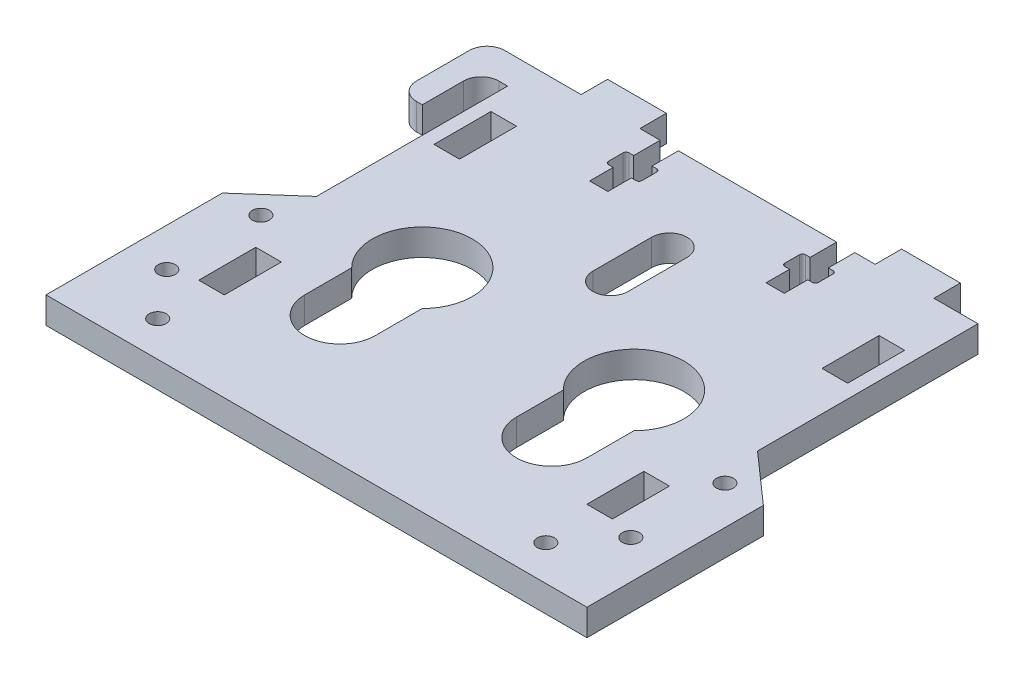
SolidWorks part; units mm, degrees
ref_plane "Front Plane" through (0, 0, 0) normal (0, 0, 1) x (1, 0, 0)
ref_plane "Top Plane" through (0, 0, 0) normal (0, 1, 0) x (1, 0, 0)
ref_plane "Right Plane" through (0, 0, 0) normal (1, 0, 0) x (0, 0, -1)
sketch "Sketch1" plane through (0, 0, 0) normal (0, 1, 0) x (1, 0, 0)
  line L1 (-37.5, 37.5) -> (37.5, 37.5)
  line L2 (-37.5, 37.5) -> (-37.5, -37.5)
  line L3 (-37.5, -37.5) -> (37.5, -37.5)
  line L4 (37.5, 37.5) -> (37.5, -37.5)
  line L5 (-37.5, 37.5) -> (37.5, -37.5) construction
  line L6 (-37.5, -37.5) -> (37.5, 37.5) construction
  point P0 (0, 0)
  dimension "D1" = 75
  dimension "D2" = 75
extrude "MainShape" add sketch "Sketch1" along normal blind 4.5
sketch "Sketch2" plane through (0, 4.5, 0) normal (0, 1, 0) x (1, 0, 0)
  line L0 (0, -37.5) -> (0, 37.5) construction
  line L1 (-37.5, -37.5) -> (37.5, -37.5) construction
  line L2 (37.5, 37.5) -> (-37.5, 37.5) construction
  line L4 (-5, 42) -> (5, 42)
  line L5 (-5, 42) -> (-5, 33)
  line L6 (-5, 33) -> (5, 33)
  line L7 (5, 42) -> (5, 33)
  line L8 (-5, 42) -> (5, 33) construction
  line L9 (-5, 33) -> (5, 42) construction
  dimension "D1" = 10
  dimension "D2" = 4.5
extrude "Tab1" [suppressed] add sketch "Sketch2" against normal through all
sketch "Sketch4" [suppressed] plane through (0, 4.5, 0) normal (0, 1, 0) x (1, 0, 0)
  line L0 (0, 42) -> (0, -37.5) construction
  line L1 (5, 42) -> (-5, 42) construction
  line L2 (-47.5, -37.5) -> (47.5, -37.5) construction
  line L3 (-40, 37.5) -> (-40, 27) construction
  line L4 (-5, 37.5) -> (-47.5, 37.5) construction
  line L5 (-38.25, 27) -> (-41.75, 27) construction
  line L6 (-41.75, 27) -> (-41.75, 37.5) construction
  line L7 (-38.25, 27) -> (-41.75, 27)
  line L8 (-41.75, 27) -> (-41.75, 29.5)
  line L9 (-41.75, 29.5) -> (-42.75, 29.5)
  line L10 (-43, 29.75) -> (-43, 33.45)
  line L11 (-42.75, 33.7) -> (-41.75, 33.7)
  line L12 (-41.75, 33.7) -> (-41.75, 37.5)
  line L13 (-41.75, 37.5) -> (-38.25, 37.5)
  line L14 (-38.25, 27) -> (-38.25, 37.5) construction
  line L15 (-38.25, 33.7) -> (-38.25, 37.5)
  line L16 (-37.25, 33.7) -> (-38.25, 33.7)
  line L17 (-37, 29.75) -> (-37, 33.45)
  line L18 (-38.25, 29.5) -> (-37.25, 29.5)
  line L19 (-38.25, 27) -> (-38.25, 29.5)
  line L20 (38.25, 27) -> (38.25, 37.5) construction
  line L21 (41.75, 27) -> (41.75, 37.5) construction
  line L22 (38.25, 27) -> (41.75, 27) construction
  line L23 (40, 37.5) -> (40, 27) construction
  line L24 (38.25, 27) -> (38.25, 29.5)
  line L25 (38.25, 29.5) -> (37.25, 29.5)
  line L26 (37, 29.75) -> (37, 33.45)
  line L27 (37.25, 33.7) -> (38.25, 33.7)
  line L28 (38.25, 33.7) -> (38.25, 37.5)
  line L29 (41.75, 37.5) -> (38.25, 37.5)
  line L30 (41.75, 33.7) -> (41.75, 37.5)
  line L31 (42.75, 33.7) -> (41.75, 33.7)
  line L32 (43, 29.75) -> (43, 33.45)
  line L33 (41.75, 29.5) -> (42.75, 29.5)
  line L34 (41.75, 27) -> (41.75, 29.5)
  line L35 (38.25, 27) -> (41.75, 27)
  arc A0 (-42.75, 29.5) -> (-43, 29.75) centre (-42.75, 29.75) cw
  arc A1 (-37, 29.75) -> (-37.25, 29.5) centre (-37.25, 29.75) cw
  arc A2 (-37.25, 33.7) -> (-37, 33.45) centre (-37.25, 33.45) cw
  arc A3 (-43, 33.45) -> (-42.75, 33.7) centre (-42.75, 33.45) cw
  arc A4 (43, 33.45) -> (42.75, 33.7) centre (42.75, 33.45) ccw
  arc A5 (37.25, 33.7) -> (37, 33.45) centre (37.25, 33.45) ccw
  arc A6 (37, 29.75) -> (37.25, 29.5) centre (37.25, 29.75) ccw
  arc A7 (42.75, 29.5) -> (43, 29.75) centre (42.75, 29.75) ccw
  point P24 (-43, 29.5)
  point P27 (-37, 29.5)
  point P30 (-37, 33.7)
  point P33 (-43, 33.7)
  point P56 (43, 33.7)
  point P57 (37, 33.7)
  point P58 (37, 29.5)
  point P59 (43, 29.5)
  dimension "D7" = 0.5
  dimension "D1" = 11
  dimension "D2" = 1.55
  dimension "D3" = 3.5
  dimension "D4" = 2.85
  dimension "D5" = 8
  dimension "D6" = 40
extrude "Cut-Extrude2" [suppressed] cut sketch "Sketch4" against normal through all
sketch "Sketch5" plane through (0, 4.5, 0) normal (0, 1, 0) x (1, 0, 0)
  line L0 (0, -37.5) -> (0, 37.5) construction
  line L1 (-37.5, -37.5) -> (37.5, -37.5) construction
  line L3 (33, 37.5) -> (33, -37.5) construction
  line L4 (37.5, 37.5) -> (-37.5, 37.5) construction
  line L5 (-33, 37.5) -> (-33, -37.5) construction
  line L6 (30.825, 27.35) -> (35.175, 27.35)
  line L7 (30.825, 27.35) -> (30.825, 17.65)
  line L8 (30.825, 17.65) -> (35.175, 17.65)
  line L9 (35.175, 27.35) -> (35.175, 17.65)
  line L10 (30.825, 27.35) -> (35.175, 17.65) construction
  line L11 (30.825, 17.65) -> (35.175, 27.35) construction
  line L12 (-30.825, 17.65) -> (-35.175, 27.35) construction
  line L13 (-30.825, 27.35) -> (-35.175, 17.65) construction
  line L14 (-35.175, 27.35) -> (-35.175, 17.65)
  line L15 (-30.825, 17.65) -> (-35.175, 17.65)
  line L16 (-30.825, 27.35) -> (-30.825, 17.65)
  line L17 (-30.825, 27.35) -> (-35.175, 27.35)
  line L18 (-37.5, 2.5) -> (37.5, 2.5) construction
  line L19 (-37.5, 37.5) -> (-37.5, -37.5) construction
  line L20 (37.5, -37.5) -> (37.5, 37.5) construction
  line L21 (-30.825, -22.35) -> (-35.175, -12.65) construction
  line L22 (-30.825, -12.65) -> (-35.175, -22.35) construction
  line L23 (30.825, -12.65) -> (35.175, -22.35) construction
  line L24 (30.825, -22.35) -> (35.175, -12.65) construction
  line L25 (-30.825, -22.35) -> (-35.175, -22.35)
  line L26 (-30.825, -22.35) -> (-30.825, -12.65)
  line L27 (-30.825, -12.65) -> (-35.175, -12.65)
  line L28 (-35.175, -22.35) -> (-35.175, -12.65)
  line L29 (35.175, -22.35) -> (35.175, -12.65)
  line L30 (30.825, -12.65) -> (35.175, -12.65)
  line L31 (30.825, -22.35) -> (30.825, -12.65)
  line L32 (30.825, -22.35) -> (35.175, -22.35)
  line L33 (-30.825, 27.35) -> (-35.175, 17.65) construction
  line L34 (-37.5, 37.5) -> (37.5, 37.5) construction
  line L35 (37.5, 37.5) -> (-37.5, 37.5) construction
  point P10 (33, 22.5)
  point P21 (-33, 22.5)
  point P36 (-33, -17.5)
  point P37 (33, -17.5)
  dimension "D1" = 33
  dimension "D2" = 9.7
  dimension "D3" = 4.35
  dimension "D4" = 15
  dimension "D5" = 40
extrude "Cut-Extrude3" cut sketch "Sketch5" against normal through all
sketch "Sketch6" plane through (0, 4.5, 0) normal (0, 1, 0) x (1, 0, 0)
  line L0 (-18, -37.5) -> (-18, 28) construction
  line L1 (-24, -15.5) -> (-24, -7.5208)
  line L3 (-37.5, -15.5) -> (37.5, -15.5) construction
  line L4 (-37.5, 37.5) -> (-37.5, -37.5) construction
  line L5 (37.5, -37.5) -> (37.5, 37.5) construction
  line L6 (37.5, 37.5) -> (-37.5, 37.5) construction
  line L7 (-37.5, -37.5) -> (37.5, -37.5) construction
  line L8 (-12, -15.5) -> (-12, -7.5208)
  line L9 (-37.5, 37.5) -> (37.5, 37.5) construction
  arc A0 (-24, -15.5) -> (-12, -15.5) centre (-18, -15.5) ccw
  arc A2 (-12, -7.5208) -> (-24, -7.5208) centre (-18, -1.5) ccw
  dimension "D1" = 12
  dimension "D6" = 8.5
  dimension "D2" = 53
  dimension "D3" = 0
  dimension "D5" = 0
  dimension "D7" = 14
  dimension "D4" = 18
extrude "Cut-Extrude4" cut sketch "Sketch6" against normal through all
sketch "Sketch13" plane through (0, 4.5, 0) normal (0, 1, 0) x (1, 0, 0)
  line L0 (-37.5, 0) -> (-46, -7.5)
  line L1 (-37.5, 37.5) -> (-37.5, -37.5) construction
  line L2 (-46, -7.5) -> (-46, -37.5)
  line L3 (-46, -37.5) -> (-37.5, -37.5)
  line L4 (-37.5, -37.5) -> (-37.5, 0)
  line L5 (0, 37.5) -> (0, -37.5) construction
  line L6 (37.5, 37.5) -> (-37.5, 37.5) construction
  line L7 (-37.5, -37.5) -> (37.5, -37.5) construction
  line L8 (37.5, -37.5) -> (37.5, 0)
  line L9 (46, -37.5) -> (37.5, -37.5)
  line L10 (46, -7.5) -> (46, -37.5)
  line L11 (37.5, 0) -> (46, -7.5)
  line L12 (-37.5, -37.5) -> (-37.5, 0)
  line M23 (37.5, -37.5) -> (37.5, 37.5)
  line M25 (-37.5, 37.5) -> (-37.5, -37.5)
  dimension "D1" = 46
  dimension "D2" = 30
extrude "Boss-Extrude2" add sketch "Sketch13" against normal through all contours L2 L3 L0 M25 | L11 L9 L10 M23
sketch "Sketch8" plane through (0, 4.5, 0) normal (0, 1, 0) x (1, 0, 0)
  line L0 (-18, -9.5) -> (-18, -21.5) construction
  line L1 (-18, -15.5) -> (-39.46, -15.5) construction
  line L2 (-39.46, -23.5) -> (-39.46, -7.5) construction
  line L3 (-18, -21.5) -> (-18, -9.5) construction
  circle A0 centre (-39.46, -7.5) radius 1.45
  circle A1 centre (-18, -15.5) radius 6 construction
  circle A2 centre (-39.46, -23.5) radius 1.45
  dimension "D3" = 2.9
  dimension "D1" = 0
  dimension "D2" = 8
  dimension "D4" = 21.46
extrude "Cut-Extrude6" cut sketch "Sketch8" against normal through all
mirror "Mirror1" about plane through (0, 0, 0) normal (1, 0, 0) of "Cut-Extrude6", "Cut-Extrude4"
sketch "Sketch11" plane through (0, 4.5, 0) normal (0, 1, 0) x (1, 0, 0)
  line L0 (0, 37.5) -> (0, -37.5) construction
  line L1 (37.5, 37.5) -> (-37.5, 37.5) construction
  line L2 (-46, -37.5) -> (46, -37.5) construction
  line L3 (-25, 42) -> (-25, 37.5) construction
  line L4 (-30, 37.5) -> (-20, 37.5)
  line L5 (-30, 37.5) -> (-30, 42)
  line L6 (-30, 42) -> (-20, 42)
  line L7 (-20, 37.5) -> (-20, 42)
  line L8 (25, 42) -> (25, 37.5) construction
  line L9 (20, 37.5) -> (20, 42)
  line L10 (30, 42) -> (20, 42)
  line L11 (30, 37.5) -> (30, 42)
  line L12 (30, 37.5) -> (20, 37.5)
  dimension "D1" = 10
  dimension "D2" = 4.5
  dimension "D3" = 25
extrude "RearTabs" add sketch "Sketch11" against normal through all
sketch "Sketch12" plane through (0, 4.5, 0) normal (0, 1, 0) x (1, 0, 0)
  line L0 (-15, 0) -> (-15, 37.5) construction
  line L1 (20, 37.5) -> (-20, 37.5) construction
  line L2 (-13.45, 37.5) -> (-16.55, 37.5)
  line L3 (-16.55, 37.5) -> (-16.55, 33)
  line L4 (-16.55, 33) -> (-17.35, 33)
  line L5 (-17.85, 32.5) -> (-17.85, 30)
  line L6 (-17.35, 29.5) -> (-16.55, 29.5)
  line L7 (-16.55, 29.5) -> (-16.55, 25.5)
  line L8 (-16.55, 25.5) -> (-13.45, 25.5)
  line L9 (-13.45, 29.5) -> (-13.45, 25.5)
  line L10 (-12.65, 29.5) -> (-13.45, 29.5)
  line L11 (-12.15, 32.5) -> (-12.15, 30)
  line L12 (-13.45, 33) -> (-12.65, 33)
  line L13 (-13.45, 37.5) -> (-13.45, 33)
  line L14 (0, 37.5) -> (0, 23.4067) construction
  line L15 (13.45, 37.5) -> (13.45, 33)
  line L16 (13.45, 33) -> (12.65, 33)
  line L17 (12.15, 32.5) -> (12.15, 30)
  line L18 (12.65, 29.5) -> (13.45, 29.5)
  line L19 (13.45, 29.5) -> (13.45, 25.5)
  line L20 (16.55, 25.5) -> (13.45, 25.5)
  line L21 (16.55, 29.5) -> (16.55, 25.5)
  line L22 (17.35, 29.5) -> (16.55, 29.5)
  line L23 (17.85, 32.5) -> (17.85, 30)
  line L24 (16.55, 33) -> (17.35, 33)
  line L25 (16.55, 37.5) -> (16.55, 33)
  line L26 (13.45, 37.5) -> (16.55, 37.5)
  arc A0 (-17.85, 30) -> (-17.35, 29.5) centre (-17.35, 30) ccw
  arc A1 (-17.35, 33) -> (-17.85, 32.5) centre (-17.35, 32.5) ccw
  arc A2 (-12.65, 33) -> (-12.15, 32.5) centre (-12.65, 32.5) cw
  arc A3 (-12.15, 30) -> (-12.65, 29.5) centre (-12.65, 30) cw
  arc A4 (12.15, 30) -> (12.65, 29.5) centre (12.65, 30) ccw
  arc A5 (12.65, 33) -> (12.15, 32.5) centre (12.65, 32.5) ccw
  arc A6 (17.35, 33) -> (17.85, 32.5) centre (17.35, 32.5) cw
  arc A7 (17.85, 30) -> (17.35, 29.5) centre (17.35, 30) cw
  point P14 (-17.85, 29.5)
  point P17 (-17.85, 33)
  point P25 (-15, 25.5)
  point P28 (-12.15, 33)
  point P29 (-12.15, 29.5)
  point P53 (12.15, 29.5)
  point P54 (12.15, 33)
  point P55 (15, 25.5)
  point P56 (17.85, 33)
  point P57 (17.85, 29.5)
  dimension "D5" = 8
  dimension "D1" = 12
  dimension "D6" = 0.5
  dimension "D2" = 3.5
  dimension "D3" = 2.85
  dimension "D4" = 1.55
  dimension "D7" = 15
extrude "FrontScrewSlot" cut sketch "Sketch12" against normal through all
sketch "Sketch14" plane through (0, 4.5, 0) normal (0, 1, 0) x (1, 0, 0)
  line L0 (-33, 27.35) -> (-33, -37.5) construction
  line L1 (-30.825, 27.35) -> (-35.175, 27.35) construction
  line L2 (-46, -37.5) -> (46, -37.5) construction
  line L3 (-30, 37.5) -> (-37.5, 37.5) construction
  line L4 (0, 0) -> (0, -37.5) construction
  line L5 (33, 27.35) -> (33, -37.5) construction
  line L6 (-33, 27.35) -> (-33, -37.5) construction
  circle A0 centre (-33, -31.5) radius 1.45
  circle A1 centre (33, -31.5) radius 1.45
  dimension "D2" = 2.9
  dimension "D1" = 69
extrude "BraceScrews" cut sketch "Sketch14" against normal through all
sketch "Sketch15" plane through (0, 4.5, 0) normal (0, 1, 0) x (1, 0, 0)
  line L0 (0, -37.5) -> (0, 27.5) construction
  line L1 (-46, -37.5) -> (46, -37.5) construction
  line L3 (16, 27.5) -> (-16, 27.5) construction
  line L4 (-16.55, 37.5) -> (-20, 37.5) construction
  line L5 (-18.175, 32.35) -> (-13.825, 32.35)
  line L6 (-18.175, 32.35) -> (-18.175, 22.65)
  line L7 (-18.175, 22.65) -> (-13.825, 22.65)
  line L8 (-13.825, 32.35) -> (-13.825, 22.65)
  line L9 (-18.175, 32.35) -> (-13.825, 22.65) construction
  line L10 (-18.175, 22.65) -> (-13.825, 32.35) construction
  line L11 (18.175, 22.65) -> (13.825, 32.35) construction
  line L12 (18.175, 32.35) -> (13.825, 22.65) construction
  line L13 (13.825, 32.35) -> (13.825, 22.65)
  line L14 (18.175, 22.65) -> (13.825, 22.65)
  line L15 (18.175, 32.35) -> (18.175, 22.65)
  line L16 (18.175, 32.35) -> (13.825, 32.35)
  point P19 (0, 27.5)
  dimension "D1" = 16
  dimension "D2" = 4.35
  dimension "D3" = 9.7
  dimension "D4" = 10
extrude "FanTabs" [suppressed] cut sketch "Sketch15" against normal through all
sketch "Sketch16" plane through (0, 4.5, 0) normal (0, 1, 0) x (1, 0, 0)
  line L0 (0, 0) -> (0, 37.5) construction
  line L2 (0, 22.5) -> (0, 12.5) construction
  line L3 (3, 22.5) -> (3, 12.5)
  line L4 (-3, 22.5) -> (-3, 12.5)
  line L5 (13.45, 37.5) -> (-13.45, 37.5) construction
  arc A0 (3, 22.5) -> (-3, 22.5) centre (0, 22.5) ccw
  arc A1 (-3, 12.5) -> (3, 12.5) centre (0, 12.5) ccw
  point P7 (0, 17.5)
  dimension "D1" = 3
  dimension "D2" = 22.5
  dimension "D3" = 10
extrude "WiringSlot" cut sketch "Sketch16" against normal through all
sketch "Sketch17" [suppressed] plane through (0, 4.5, 0) normal (0, 1, 0) x (1, 0, 0)
  line L0 (-37.5, 14.5) -> (-37.5, 10.5) construction
  line L3 (-37.5, 37.5) -> (-37.5, 0) construction
  line L4 (-36, 14.5) -> (-36, 10.5)
  line L5 (-39, 14.5) -> (-39, 10.5)
  line L6 (-37.5, 14.5) -> (-37.5, 10.5) construction
  line L7 (-34, 14.5) -> (-34, 10.5)
  line L8 (-41, 14.5) -> (-41, 10.5)
  line L9 (-41, 12.5) -> (-37.5, 12.5) construction
  line L10 (0, 0) -> (0, -12.1805) construction
  arc A0 (-36, 14.5) -> (-39, 14.5) centre (-37.5, 14.5) ccw
  arc A1 (-39, 10.5) -> (-36, 10.5) centre (-37.5, 10.5) ccw
  arc A2 (-34, 14.5) -> (-41, 14.5) centre (-37.5, 14.5) ccw
  arc A3 (-41, 10.5) -> (-34, 10.5) centre (-37.5, 10.5) ccw
  point P4 (-37.5, 12.5)
  point P10 (-37.5, 12.5)
  dimension "D4" = 4
  dimension "D5" = 25
  dimension "D1" = 0
  dimension "D2" = 2
  dimension "D3" = 1.5
extrude "Boss-Extrude3" [suppressed] add sketch "Sketch17" against normal through all
mirror "Mirror2" [suppressed] about plane through (0, 0, 0) normal (1, 0, 0)
sketch "Sketch18" [suppressed] plane through (0, 4.5, 0) normal (0, 1, 0) x (1, 0, 0)
  line L0 (0, -37.5) -> (0, 47.6111) construction
  line L1 (-45, -37.5) -> (45, -37.5) construction
  line L2 (-12, 2) -> (-12, -19.46) construction
  line L3 (-4, -19.46) -> (-20, -19.46) construction
  circle A0 centre (-12, 2) radius 5
  circle A1 centre (-20, -19.46) radius 1.45
  circle A2 centre (-4, -19.46) radius 1.45
  dimension "D2" = 8
  dimension "D4" = 21.46
  dimension "D1" = 2.9
  dimension "D3" = 10
  dimension "D5" = 12
  dimension "D6" = 2
extrude "Cut-Extrude7" [suppressed] cut sketch "Sketch18" against normal through all
mirror "Mirror3" [suppressed] about plane through (0, 0, 0) normal (1, 0, 0)
sketch "Sketch19" [suppressed] plane through (0, 4.5, 0) normal (0, 1, 0) x (1, 0, 0)
  line L0 (-17, 2) -> (-7, 2) construction
  line L1 (-12, 2) -> (-4, 2) construction
  line L2 (-12, 4) -> (-4, 4)
  line L3 (-12, 0) -> (-4, 0)
  line L4 (-12, 7) -> (-12, -3) construction
  line L5 (0, 0) -> (0, 6.8806) construction
  line L6 (12, 7) -> (12, -3) construction
  line L7 (17, 2) -> (7, 2) construction
  line L8 (12, 2) -> (4, 2) construction
  line L9 (12, 4) -> (4, 4)
  line L10 (12, 0) -> (4, 0)
  circle A0 centre (-12, 2) radius 5 construction
  arc A1 (-12, 4) -> (-12, 0) centre (-12, 2) ccw
  arc A2 (-4, 0) -> (-4, 4) centre (-4, 2) ccw
  arc A3 (12, 4) -> (12, 0) centre (12, 2) cw
  arc A4 (4, 0) -> (4, 4) centre (4, 2) cw
  point P6 (-8, 2)
  point P23 (8, 2)
  dimension "D1" = 2
  dimension "D2" = 8
extrude "Cut-Extrude8" [suppressed] cut sketch "Sketch19" against normal through all
sketch "Sketch20" plane through (0, 4.5, 0) normal (0, 1, 0) x (1, 0, 0)
  line L0 (0, 0) -> (0, -37.5) construction
  line L1 (-46, -37.5) -> (46, -37.5) construction
  line L2 (-26.9758, -32.9017) -> (-26.9758, -26.6196)
  line L3 (-26.9758, -26.6196) -> (-6.5592, -26.6196)
  line L4 (-6.5592, -26.6196) -> (-6.5592, 9.4097)
  line L5 (-6.5592, 9.4097) -> (6.5592, 9.4097)
  line L6 (-26.9758, -32.9017) -> (26.9758, -32.9017)
  line L7 (6.5592, -26.6196) -> (6.5592, 9.4097)
  line L8 (26.9758, -26.6196) -> (6.5592, -26.6196)
  line L9 (26.9758, -32.9017) -> (26.9758, -26.6196)
  point P12 (0, -32.9017)
  point P13 (0, 9.4097)
extrude "Cut-Extrude9" [suppressed] cut sketch "Sketch20" against normal through all
sketch "Sketch21" plane through (0, 4.5, 0) normal (0, 1, 0) x (1, 0, 0)
  line L0 (-46, -37.5) -> (-46, 37.5) construction
  line L1 (-37, 37.5) -> (-43, 37.5)
  line L4 (-46, 34.5) -> (-46, 25.5)
  line L5 (-43, 22.5) -> (-42, 22.5)
  line L6 (-42, 22.5) -> (-42, 29.5)
  line L7 (-39, 32.5) -> (-37, 32.5)
  line L9 (-37, 32.5) -> (-37, 37.5)
  line L10 (-30, 37.5) -> (-37.5, 37.5) construction
  line L11 (-37.5, 37.5) -> (-37.5, 0) construction
  arc A0 (-42, 29.5) -> (-39, 32.5) centre (-39, 29.5) cw
  arc A1 (-46, 25.5) -> (-43, 22.5) centre (-43, 25.5) ccw
  arc A2 (-43, 37.5) -> (-46, 34.5) centre (-43, 34.5) ccw
  point P19 (-46, 22.5)
  point P24 (-42, 37.5)
  dimension "D1" = 3
  dimension "D4" = 3
  dimension "D2" = 15
  dimension "D3" = 5
  dimension "D5" = 4
  dimension "D6" = 0.5
  dimension "D7" = 0
extrude "Boss-Extrude4" add sketch "Sketch21" against normal through all
sketch "Sketch22" plane through (0, 4.5, 0) normal (0, 1, 0) x (1, 0, 0)
  line L0 (-46, -7.5) -> (-46, 13.5)
  line L1 (-43, 16.5) -> (-42, 16.5)
  line L2 (-42, 16.5) -> (-42, -3.9706)
  line L3 (-37.5, 0) -> (-46, -7.5) construction
  line L4 (-42, -3.9706) -> (-46, -7.5)
  line L5 (-46, 16.5) -> (-46, 28.3122) construction
  line L6 (-46, 34.5) -> (-46, 25.5) construction
  line L7 (-42, 22.6875) -> (-42, 12.0504) construction
  line L8 (-42, 22.5) -> (-42, 29.5) construction
  arc A0 (-46, 13.5) -> (-43, 16.5) centre (-43, 13.5) cw
  dimension "D2" = 3
  dimension "D1" = 6
extrude "Boss-Extrude5" [suppressed] add sketch "Sketch22" against normal through all
mirror "Mirror6" [suppressed] about plane through (0, 0, 0) normal (1, 0, 0)
equation "\"X-ROD-SPACING\"=45"
equation "\"Y-ROD-SPACING\"=75"
equation "\"Z-ROD-SPACING\"=17.5"
equation "\"Y-BED-OFFSET\"=2"
equation "\"Y-BED-ROD-INSET\"=3.5"
equation "\"Y-BED-SCREW-SPACING\"=209"
equation "\"Y-BED-SCREW-CUTOUT-SLOT-HEIGHT\"=2.5"
equation "\"T-SLOT-NUT-FILLET-RADIUS\"=0.5"
equation "\"T-SLOT-SCREW-SHAFT-RADIUS\"=1.55"
equation "\"T-SLOT-SCREW-SHAFT-CUTOUT-LENGTH\"=11"
equation "\"T-SLOT-NUT-DEPTH\"=3.5"
equation "\"T-SLOT-NUT-WIDTH\"=2.85"
equation "\"T-SLOT-NUT-END-DISTANCE\"=8"
equation "\"ACRYLIC-THICKNESS\"=10"
equation "\"ACRYLIC-THICKNESS2\"=4.5"
equation "\"ACRYLIC-TAB-CUTOUT-SIZE\"=\"ACRYLIC-THICKNESS\"+\"ACRYLIC-TAB-TOLERANCE\"*2"
equation "\"ACRYLIC-TAB-WIDTH\"=\"ACRYLIC-THICKNESS\""
equation "\"ACRYLIC-M3-HOLE\"=2.9"
equation "\"SMOOTHROD-CAP-SCREW-DISTANCE\"=20"
equation "\"FRAME-WIDTH-INNER\"=370"
equation "\"NEMA17-HOLE-SPACING\"=31"
equation "\"NEMA17-CENTRAL-CUTOUT\"=22.5"
equation "\"Z-BRACKET-REACH\"=57"
equation "\"Z-ROD-INSET\"=13.5"
equation "\"TOP-BRACKET-SPACING\"=40"
equation "\"SMOOTHROD-X-LENGTH\"=350"
equation "\"SMOOTHROD-Y-LENGTH\"=350"
equation "\"SMOOTHROD-Z-LENGTH\"=350"
equation "\"SMOOTHROD-TIGHTENING-HEADROOM\"=.25"
equation "\"LEADSCREW-Z-LENGTH\"=300"
equation "\"SCREW-LENGTH-FRAME\"=\"ACRYLIC-THICKNESS\" + 10"
equation "\"SCREW-LENGTH-MOTOR\"=\"ACRYLIC-THICKNESS\" + 5"
equation "\"SCREW-LENGTH-EXTRUDER\"=28"
equation "\"SCREW-HEAD-RADIUS\"=6"
equation "\"PRINTED-X-SMOOTHROD-DIAMETER\"=8.8"
equation "\"PRINTED-X-SMOOTHROD-CUTOUT\"=10"
equation "\"PRINTED-X-BASE-HEIGHT\"=10"
equation "\"PRINTED-LM8UU-CUTOUT-SIZE\"=15.5"
equation "\"PRINTED-LM8UU-CUTOUT-LENGTH\"=24.5"
equation "\"PRINTED-X-IDLER-HEIGHT\"=16"
equation "\"PSU-MOUNTING-WIDTH\"=50"
equation "\"PSU-MOUNTING-HEIGHT\"=150"
equation "\"Y-BELT-TO-ROD-DISTANCE\"=20"
equation "\"SPOOL-HOLDER-ROD-SPACING\"=150"
equation "\"ACRYLIC-X-CARRIAGE-WIDTH\"=55"
equation "\"ACRYLIC-X-CARRIAGE-HEIGHT\"=75"
equation "\"ACRYLIC-X-CARRIAGE-SCREW-SPACING-X\"=15"
equation "\"ACRYLIC-X-CARRIAGE-SCREW-SPACING-Y\"=33"
equation "\"ACRYLIC-X-CARRIAGE-CENTER-TAB-SPACING\"=14"
equation "\"D1@MainShape\" = \"ACRYLIC-THICKNESS2\""
equation "\"D1@Sketch2\"=\"ACRYLIC-TAB-WIDTH\""
equation "\"D2@Sketch2\"=\"ACRYLIC-THICKNESS2\""
equation "\"D1@Sketch4\"=\"T-SLOT-SCREW-SHAFT-CUTOUT-LENGTH\""
equation "\"D2@Sketch4\"=\"T-SLOT-SCREW-SHAFT-RADIUS\""
equation "\"D3@Sketch4\"=\"T-SLOT-NUT-DEPTH\""
equation "\"D4@Sketch4\"=\"T-SLOT-NUT-WIDTH\""
equation "\"D5@Sketch4\"=\"T-SLOT-NUT-END-DISTANCE\""
equation "\"D7@Sketch4\"=\"T-SLOT-NUT-FILLET-RADIUS\""
equation "\"ACRYLIC-X-CARRIAGE-EXTRUDER-SHELF-DEPTH\"=\"ACRYLIC-X-CARRIAGE-EXTRUDER-OFFSET\" + 28"
equation "\"ACRYLIC-X-CARRIAGE-LM8UU-CUTOUT-WIDTH\"=24.25"
equation "\"ACRYLIC-X-CARRIAGE-EXTRUDER-BRACE-SPACING\"=23"
equation "\"ACRYLIC-X-CARRIAGE-EXTRUDER-BRACE-TAB-OFFSET\"=20"
equation "\"ACRYLIC-X-CARRIAGE-EXTRUDER-BRACE-HEIGHT\"=35"
equation "\"ACRYLIC-X-CARRIAGE-EXTRUDER-BRACE-SCREW-SPACING\"=22"
equation "\"D2@Sketch5\"=\"ACRYLIC-THICKNESS2-TAB-CUTOUT-HEIGHT\""
equation "\"D3@Sketch5\"=\"ACRYLIC-THICKNESS2-TAB-CUTOUT-WIDTH\""
equation "\"D3@Sketch8\"=\"ACRYLIC-M3-HOLE\""
equation "\"ACRYLIC-X-CARRIAGE-EXTRUDER-ANGLE\"=90"
equation "\"ACRYLIC-X-CARRIAGE-EXTRUDER-OFFSET\"=26"
equation "\"ACRYLIC-TAB-TOLERANCE\"=-.05"
equation "\"ACRYLIC-X-CARRIAGE-DUAL-WIDTH-MULTIPLIER\"=1.65"
equation "\"ACRYLIC-X-CARRIAGE-DUAL-HOTEND-SPACING\"=42"
equation "\"ACRYLIC-X-CARRIAGE-DUAL-WIDTH\"=75"
equation "\"ACRYLIC-X-CARRIAGE-DUAL-HOTEND-SEPARATION\"=36"
equation "\"ACRYLIC-X-CARRIAGE-DUAL-MOUNT-PLATE-DEPTH\"=75"
equation "\"ACRYLIC-X-CARRIAGE-DUAL-MOUNT-BRACE-WIDTH\"=33"
equation "\"D1@Sketch5\"=\"ACRYLIC-X-CARRIAGE-DUAL-MOUNT-BRACE-WIDTH\""
equation "\"ACRYLIC-X-CARRIAGE-DUAL-MOUNT-SCREW-WIDTH\"=40"
equation "\"D6@Sketch4\"=\"ACRYLIC-X-CARRIAGE-DUAL-MOUNT-SCREW-WIDTH\""
equation "\"D1@Sketch1\"=\"ACRYLIC-X-CARRIAGE-DUAL-WIDTH\""
equation "\"D2@Sketch1\"=\"ACRYLIC-X-CARRIAGE-DUAL-MOUNT-PLATE-DEPTH\""
equation "\"D4@Sketch6\"=\"ACRYLIC-X-CARRIAGE-DUAL-HOTEND-SEPARATION\"/2"
equation "\"D1@Sketch11\"=\"ACRYLIC-TAB-WIDTH\""
equation "\"D2@Sketch11\"=\"ACRYLIC-THICKNESS2\""
equation "\"D1@Sketch12\"=\"T-SLOT-SCREW-SHAFT-CUTOUT-LENGTH\"+1"
equation "\"D2@Sketch12\"=\"T-SLOT-NUT-DEPTH\""
equation "\"D3@Sketch12\"=\"T-SLOT-NUT-WIDTH\""
equation "\"D4@Sketch12\"=\"T-SLOT-SCREW-SHAFT-RADIUS\""
equation "\"D5@Sketch12\"=\"T-SLOT-NUT-END-DISTANCE\""
equation "\"D6@Sketch12\"=\"T-SLOT-NUT-FILLET-RADIUS\""
equation "\"D2@Sketch14\"=\"ACRYLIC-M3-HOLE\""
equation "\"D2@Sketch15\"=\"ACRYLIC-THICKNESS2-TAB-CUTOUT-WIDTH\""
equation "\"D3@Sketch15\"=\"ACRYLIC-THICKNESS2-TAB-CUTOUT-HEIGHT\""
equation "\"KERF\"=0.075"
equation "\"PRINTED-M3-HOLE\"=3.5"
equation "\"PRINTED-M3-NUT-AF\"=6.25"
equation "\"ACRYLIC-X-CARRIAGE-LM8UU-CUTOUT-HEIGHT\"=11.0"
equation "\"ACRYLIC-X-CARRIAGE-DUAL-FAN-OFFSET\"=52"
equation "\"ACRYLIC-X-CARRIAGE-DUAL-FAN-HEIGHT\"=20"
equation "\"BLOWER-FAN-WIDTH\"=15"
equation "\"ACRYLIC-THICKNESS-TAB-CUTOUT-WIDTH\"=\"ACRYLIC-THICKNESS\"-\"KERF\"*2"
equation "\"ACRYLIC-THICKNESS-TAB-CUTOUT-HEIGHT\"=\"ACRYLIC-TAB-WIDTH\"-\"KERF\"*4"
equation "\"ACRYLIC-THICKNESS2-TAB-CUTOUT-WIDTH\"=\"ACRYLIC-THICKNESS2\"-\"KERF\"*2"
equation "\"ACRYLIC-THICKNESS2-TAB-CUTOUT-HEIGHT\"=\"ACRYLIC-TAB-WIDTH\"-\"KERF\"*4"
equation "\"D1@Sketch18\"=\"ACRYLIC-M3-HOLE\""
equation "\"D7@Sketch12\"=\"ACRYLIC-X-CARRIAGE-SCREW-SPACING-X\""
